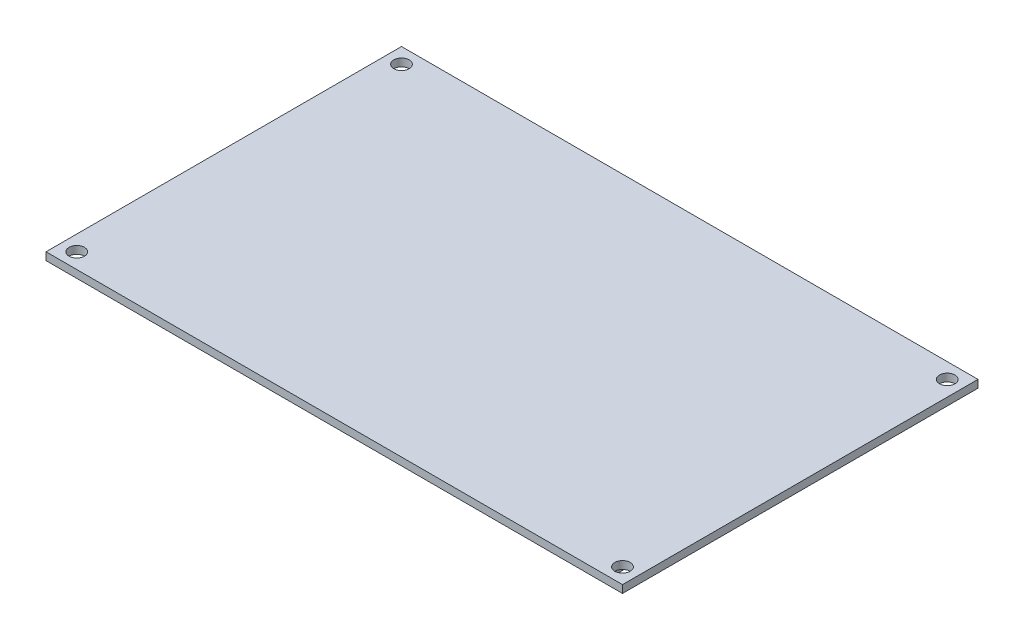
SolidWorks part; units mm, degrees
ref_plane "前视基准面" through (0, 0, 0) normal (0, 0, 1) x (1, 0, 0)
ref_plane "上视基准面" through (0, 0, 0) normal (0, 1, 0) x (1, 0, 0)
ref_plane "右视基准面" through (0, 0, 0) normal (1, 0, 0) x (0, 0, -1)
sketch "草图1" plane through (0, 0, 0) normal (0, 1, 0) x (1, 0, 0)
  line L0 (-62.9052, 0) -> (96.7946, 0) construction
  line L1 (-60, 37) -> (60, 37)
  line L2 (-60, 37) -> (-60, -37)
  line L3 (-60, -37) -> (60, -37)
  line L4 (60, 37) -> (60, -37)
  line L7 (0, 51.6604) -> (0, -43.1788) construction
  circle A0 centre (-56.8, 33.8) radius 1.6
  circle A2 centre (-56.8, -33.8) radius 1.6
  circle A3 centre (56.8, -33.8) radius 1.6
  circle A4 centre (56.8, 33.8) radius 1.6
  point P0 (0, 0)
  point P18 (60, 0)
  point P19 (0, 37)
  dimension "D4" = 3.2
  dimension "D5" = 56.8
  dimension "D1" = 120
  dimension "D2" = 74
  dimension "D3" = 33.8
extrude "凸台-拉伸2" add sketch "草图1" along normal blind 1.6
sketch "草图2" plane through (0, 0, 0) normal (0, -1, 0) x (1, 0, 0)
  line L1 (52.75, -33.6) -> (-52.75, -33.6)
  line L2 (52.75, -33.6) -> (52.75, 33.6)
  line L3 (52.75, 33.6) -> (-52.75, 33.6)
  line L4 (-52.75, -33.6) -> (-52.75, 33.6)
  line L5 (52.75, -33.6) -> (-52.75, 33.6) construction
  line L6 (52.75, 33.6) -> (-52.75, -33.6) construction
  point P0 (0, 0)
  dimension "D1" = 105.5
  dimension "D2" = 67.2
extrude "凸台-拉伸3" add sketch "草图2" along normal blind 3.1
